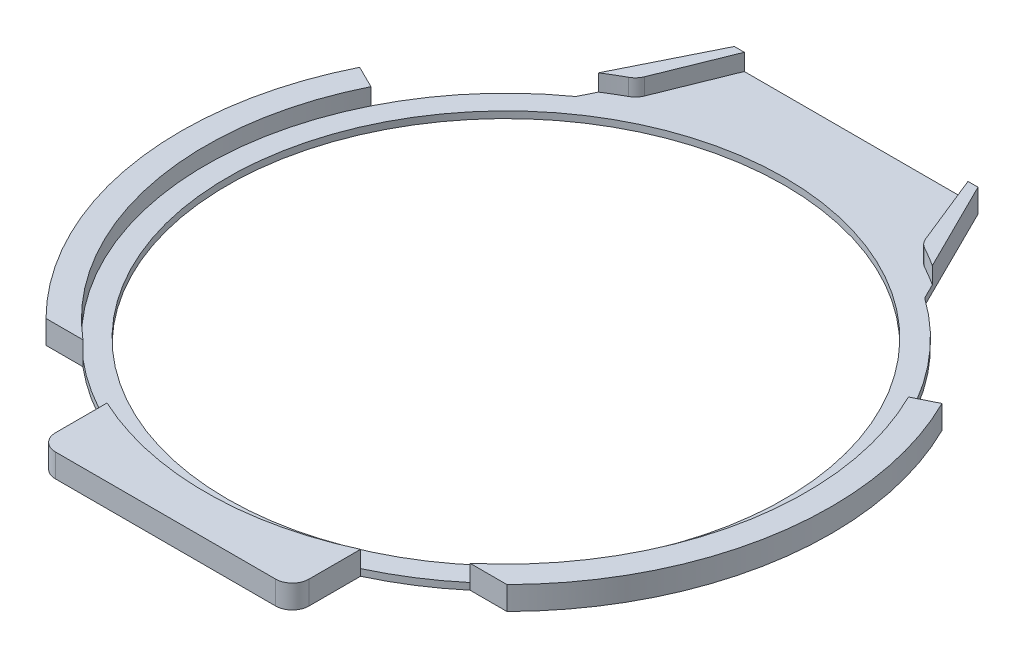
SolidWorks part; units mm, degrees
ref_plane "Front Plane" through (0, 0, 0) normal (0, 0, 1) x (1, 0, 0)
ref_plane "Top Plane" through (0, 0, 0) normal (0, 1, 0) x (1, 0, 0)
ref_plane "Right Plane" through (0, 0, 0) normal (1, 0, 0) x (0, 0, -1)
sketch "Sketch1" plane through (0, 0, 0) normal (0, 1, 0) x (1, 0, 0)
  line L0 (0, 18.5) -> (0, 19.7) construction
  line L1 (-6.5, 19.7) -> (6.5, 19.7) construction
  line L2 (6.5, 19.7) -> (8, 16.6808) construction
  line L3 (-6.5, 19.7) -> (-8, 16.6808) construction
  line L4 (0, 18.5) -> (0, -18.5) construction
  line L5 (-8, 16.6808) -> (8, 16.6808) construction
  line L6 (11, 14.8745) -> (-11, 14.8745) construction
  line L8 (0, 19.7) -> (0, 21.2) construction
  line L11 (12.5, 16.8745) -> (-12.5, 16.8745) construction
  line L15 (-21, 0) -> (21, 0) construction
  line L19 (8.5453, 23) -> (11.8004, 16.4483) construction
  line L20 (-8.5453, 23) -> (8.5453, 23) construction
  line L21 (-8.5453, 23) -> (-11.8004, 16.4483) construction
  line L22 (-8.8983, 22.2895) -> (-11.1225, 17.8126) construction
  line L23 (-7.3057, 21) -> (-10.0092, 15.5584)
  line L24 (-7.3057, 21) -> (7.3057, 21)
  line L25 (7.3057, 21) -> (10.0092, 15.5584)
  line L26 (-7.3057, 21) -> (-9.1642, 17.2592) construction
  line L27 (7.3057, 21) -> (9.1642, 17.2592) construction
  line L28 (7.3057, -21) -> (10.0092, -15.5584) construction
  line L30 (-7.3057, -21) -> (-10.0092, -15.5584) construction
  line L31 (8.8983, 22.2895) -> (11.1225, 17.8126) construction
  line L32 (8.8983, -22.2895) -> (11.1225, -17.8126) construction
  line L33 (-8.8983, -22.2895) -> (-11.1225, -17.8126) construction
  line L34 (0, 0) -> (-18.9123, 14.7759) construction
  line L35 (-19.1596, 11.7966) -> (-17.8823, 11.0101) construction
  line L36 (-16.0813, 15.7366) -> (-15.0092, 14.6875) construction
  line L37 (19.1596, 11.7966) -> (17.8823, 11.0101) construction
  line L38 (16.0813, 15.7366) -> (15.0092, 14.6875) construction
  line L39 (-7.6, -20.4077) -> (-7.6, -16.8668) construction
  line L41 (7.6, -20.4077) -> (7.6, -16.8668) construction
  line L42 (-7.6, -20.4077) -> (-7.6, -13.7584) construction
  line L43 (-7.6, -13.7584) -> (-12.3675, -13.7584) construction
  line L44 (7.6, -20.4077) -> (7.6, -13.7584) construction
  line L45 (7.6, -13.7584) -> (12.3675, -13.7584) construction
  line L48 (0, 0) -> (-20.3532, -12.7181) construction
  line L49 (-20.8968, -8.3411) -> (-19.5037, -7.785) construction
  line L50 (-16.6575, -15.1254) -> (-15.547, -14.1171) construction
  line L51 (16.6575, -15.1254) -> (15.547, -14.1171) construction
  line L52 (20.8968, -8.3411) -> (19.5037, -7.785) construction
  line L53 (10.0092, 15.5584) -> (10.4618, 14.6476)
  line L54 (19.1596, 11.7966) -> (18.8002, 9.3569) construction
  line L55 (0, 0) -> (18.8002, 9.3569) construction
  line L56 (16.1145, 8.0202) -> (17.4574, 8.6885)
  line L57 (20.8968, -8.3411) -> (20.1249, -5.9989) construction
  line L58 (13.8186, -13.7584) -> (11.6063, -13.7584)
  line L60 (7.6, -20.4077) -> (7.6, -16.3169)
  line L61 (-10.0092, 15.5584) -> (-10.4618, 14.6476)
  line L62 (-16.1145, 8.0202) -> (-17.4574, 8.6885)
  line L63 (-13.8186, -13.7584) -> (-11.6063, -13.7584)
  line L64 (-7.6, -20.4077) -> (-7.6, -16.3169)
  line L66 (7.6, -20.4077) -> (-7.6, -20.4077)
  circle A0 centre (0, 0) radius 18.5 construction
  circle A1 centre (0, 0) radius 17.5 construction
  circle A3 centre (0, 0) radius 21 construction
  circle A4 centre (0, 0) radius 24 construction
  arc A9 (-19.1596, 11.7966) -> (-16.0813, 15.7366) centre (0, 0) cw construction
  arc A10 (19.1596, 11.7966) -> (16.0813, 15.7366) centre (0, 0) ccw construction
  circle A11 centre (-16.1542, 12.6211) radius 0.8 construction
  circle A12 centre (16.1542, 12.6211) radius 0.8 construction
  circle A13 centre (-9.1959, -17.1955) radius 0.8 construction
  circle A14 centre (9.1959, -17.1955) radius 0.8 construction
  arc A15 (-20.8968, -8.3411) -> (-16.6575, -15.1254) centre (0, 0) ccw construction
  arc A16 (20.8968, -8.3411) -> (16.6575, -15.1254) centre (0, 0) cw construction
  circle A17 centre (0, 0) radius 16.7
  circle A18 centre (0, 0) radius 18 construction
  circle A19 centre (0, 0) radius 19.5 construction
  arc A20 (10.4618, 14.6476) -> (16.1145, 8.0202) centre (0, 0) cw
  arc A21 (17.4574, 8.6885) -> (13.8186, -13.7584) centre (0, 0) cw
  arc A22 (11.6063, -13.7584) -> (7.6, -16.3169) centre (0, 0) cw
  arc A23 (-10.4618, 14.6476) -> (-16.1145, 8.0202) centre (0, 0) ccw
  arc A24 (-17.4574, 8.6885) -> (-13.8186, -13.7584) centre (0, 0) ccw
  arc A25 (-11.6063, -13.7584) -> (-7.6, -16.3169) centre (0, 0) ccw
  point P8 (0, 19.7)
  point P40 (-17.7302, 13.8524)
  point P75 (-19.0811, -11.9232)
  dimension "D1" = 37
  dimension "D10" = 42
  dimension "D13" = 48
  dimension "D14" = 22.5
  dimension "D16" = 1.6
  dimension "D20" = 1.6
  dimension "D23" = 22.5
  dimension "D25" = 33.4
  dimension "D2" = 38.2
  dimension "D3" = 13
  dimension "D4" = 16
  dimension "D6" = 22
  dimension "D7" = 1.5
  dimension "D9" = 25
  dimension "D12" = 52
  dimension "D15" = 5
  dimension "D17" = 20.5
  dimension "D18" = 7.6
  dimension "D19" = 1.8
  dimension "D21" = 19.5
  dimension "D22" = 32
  dimension "D24" = 8
  dimension "D28" = 50
  dimension "D29" = 50
  dimension "D5" = 1
  dimension "D8" = 1.3
  dimension "D11" = 2
  dimension "D26" = 0.5
  dimension "D27" = 1
extrude "Boss-Extrude1" add sketch "Sketch1" along normal blind 0.4
sketch "Sketch2" plane through (0, 0.4, 0) normal (0, 1, 0) x (1, 0, 0)
  line L0 (-8.561, 16.4) -> (-6.7057, 21)
  line L2 (8.561, 16.4) -> (6.7057, 21)
  line L4 (7.3057, 21) -> (-7.3057, 21) construction
  line L5 (-7.3057, 21) -> (-6.7057, 21)
  line L6 (6.7057, 21) -> (7.3057, 21)
  line L14 (-16.1145, 8.0202) -> (-17.4574, 8.6885)
  line L15 (-10.0092, 15.5584) -> (-10.4618, 14.6476)
  line L16 (-7.3057, 21) -> (-10.0092, 15.5584)
  line L17 (7.3057, 21) -> (-7.3057, 21)
  line L18 (10.0092, 15.5584) -> (7.3057, 21)
  line L19 (10.4618, 14.6476) -> (10.0092, 15.5584)
  line L20 (17.4574, 8.6885) -> (16.1145, 8.0202)
  line L21 (11.6063, -13.7584) -> (13.8186, -13.7584)
  line L22 (7.6, -20.4077) -> (7.6, -16.3169)
  line L23 (-7.6, -20.4077) -> (7.6, -20.4077)
  line L24 (-7.6, -20.4077) -> (7.6, -20.4077)
  line L26 (-7.6, -16.3169) -> (-7.6, -20.4077)
  line L27 (-13.8186, -13.7584) -> (-11.6063, -13.7584)
  line L28 (-16.1145, 8.0202) -> (-17.4574, 8.6885)
  line L29 (-10.0092, 15.5584) -> (-10.4618, 14.6476) construction
  line L30 (-7.3057, 21) -> (-10.0092, 15.5584)
  line L31 (7.3057, 21) -> (-7.3057, 21) construction
  line L32 (10.0092, 15.5584) -> (7.3057, 21)
  line L33 (10.4618, 14.6476) -> (10.0092, 15.5584) construction
  line L34 (17.4574, 8.6885) -> (16.1145, 8.0202)
  line L35 (11.6063, -13.7584) -> (13.8186, -13.7584)
  line L36 (7.6, -20.4077) -> (7.6, -16.3169)
  line L40 (-7.6, -16.3169) -> (-7.6, -20.4077)
  line L41 (-13.8186, -13.7584) -> (-11.6063, -13.7584)
  arc A0 (-16.1145, 8.0202) -> (-11.6063, -13.7584) centre (0, 0) ccw
  circle A1 centre (0, 0) radius 16.7
  circle A2 centre (0, 0) radius 16.7 construction
  arc A3 (-7.6, -16.3169) -> (7.6, -16.3169) centre (0, 0) ccw
  arc A4 (16.1145, 8.0202) -> (11.6063, -13.7584) centre (0, 0) cw
  arc A5 (-10.0092, 15.5584) -> (-8.561, 16.4) centre (0, 0) cw
  arc A6 (10.0092, 15.5584) -> (8.561, 16.4) centre (0, 0) ccw
  arc A8 (-10.4618, 14.6476) -> (-16.1145, 8.0202) centre (0, 0) ccw
  arc A9 (16.1145, 8.0202) -> (10.4618, 14.6476) centre (0, 0) ccw
  arc A10 (13.8186, -13.7584) -> (17.4574, 8.6885) centre (0, 0) ccw
  arc A11 (7.6, -16.3169) -> (11.6063, -13.7584) centre (0, 0) ccw
  arc A12 (-11.6063, -13.7584) -> (-7.6, -16.3169) centre (0, 0) ccw
  arc A13 (-17.4574, 8.6885) -> (-13.8186, -13.7584) centre (0, 0) ccw
  arc A14 (-10.4618, 14.6476) -> (-16.1145, 8.0202) centre (0, 0) ccw construction
  arc A15 (16.1145, 8.0202) -> (10.4618, 14.6476) centre (0, 0) ccw construction
  arc A16 (13.8186, -13.7584) -> (17.4574, 8.6885) centre (0, 0) ccw
  arc A17 (7.6, -16.3169) -> (11.6063, -13.7584) centre (0, 0) ccw construction
  arc A18 (-11.6063, -13.7584) -> (-7.6, -16.3169) centre (0, 0) ccw construction
  arc A19 (-17.4574, 8.6885) -> (-13.8186, -13.7584) centre (0, 0) ccw
  dimension "D3" = 4.6
  dimension "D4" = 0.6
  dimension "D5" = 0.6
  dimension "D1" = 0
  dimension "D2" = 0
extrude "Boss-Extrude3" add sketch "Sketch2" along normal blind 1
fillet "Fillet1" radius 1 4 edges at (7.6, 0.7, 20.4077) (-7.6, 0.7, 20.4077) (8.561, 0.9, -16.4) (-8.561, 0.9, -16.4)
equation "\"D20@Sketch1\"=\"D16@Sketch1\""
equation "\"D23@Sketch1\"=\"D14@Sketch1\""
equation "\"D29@Sketch1\"=\"D28@Sketch1\""
equation "\"D5@Sketch2\"=\"D4@Sketch2\""
